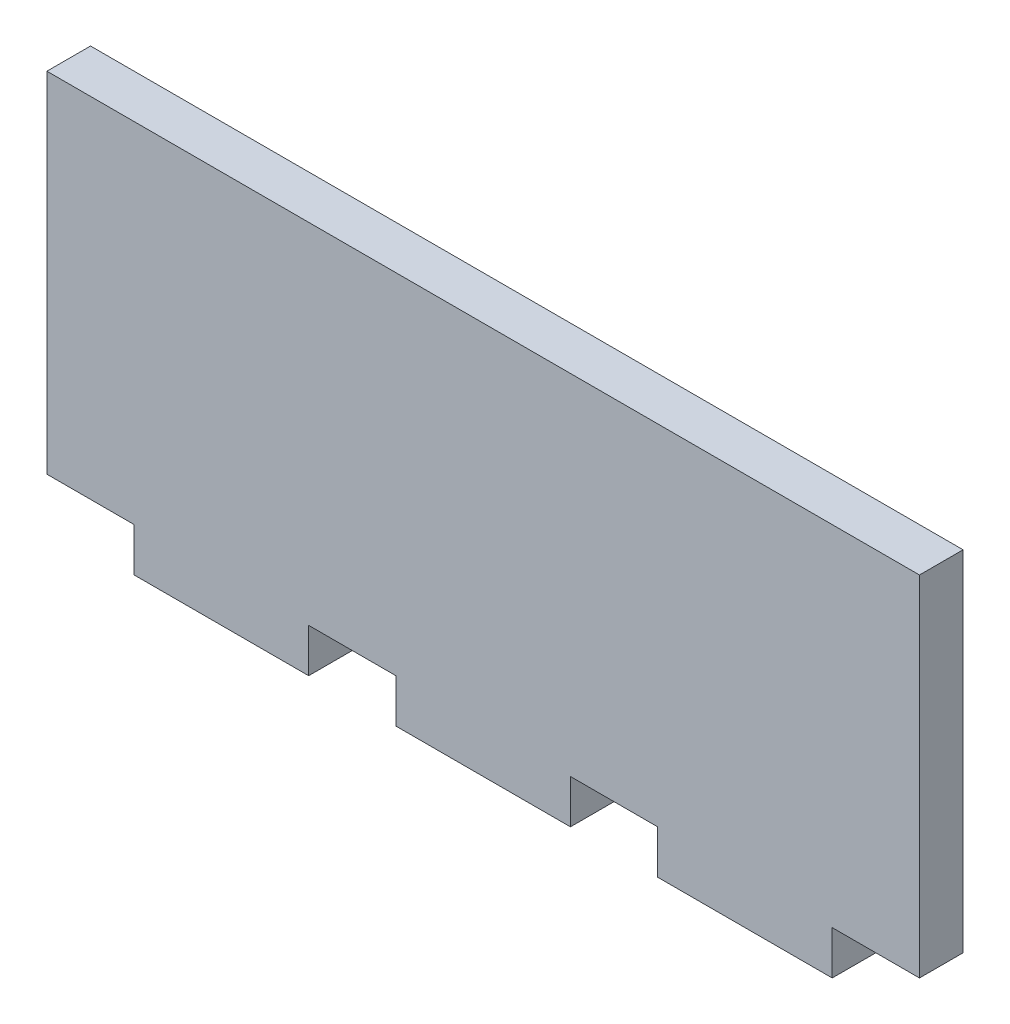
SolidWorks part; units mm, degrees
ref_plane "Plan de face" through (0, 0, 0) normal (0, 0, 1) x (1, 0, 0)
ref_plane "Plan de dessus" through (0, 0, 0) normal (0, 1, 0) x (1, 0, 0)
ref_plane "Plan de droite" through (0, 0, 0) normal (1, 0, 0) x (0, 0, -1)
sketch "Esquisse1" plane through (0, 0, 0) normal (0, 0, 1) x (1, 0, 0)
  line L0 (0, 33.3756) -> (0, -23.9848) construction
  line L1 (-50, 22.5) -> (50, 22.5)
  line L2 (-50, 22.5) -> (-50, -17.5)
  line L4 (50, 22.5) -> (50, -17.5)
  line L9 (-40, -22.5) -> (-20, -22.5)
  line L13 (-50, -17.5) -> (-40, -17.5)
  line L14 (-40, -22.5) -> (-40, -17.5)
  line L15 (40, -22.5) -> (40, -17.5)
  line L16 (50, -17.5) -> (40, -17.5)
  line L17 (20, -22.5) -> (20, -17.5)
  line L19 (-10, -22.5) -> (-10, -17.5)
  line L20 (-10, -17.5) -> (-20, -17.5)
  line L21 (-20, -22.5) -> (-20, -17.5)
  line L22 (10, -22.5) -> (10, -17.5)
  line L23 (10, -17.5) -> (20, -17.5)
  line L27 (-10, -22.5) -> (10, -22.5)
  line L28 (20, -22.5) -> (40, -22.5)
  point P1 (-45, -17.5)
  point P2 (-15, -17.5)
  dimension "D1" = 20
  dimension "D2" = 10
  dimension "D3" = 10
  dimension "D4" = 5
  dimension "D5" = 50
  dimension "D6" = 22.5
  dimension "D7" = 5
  dimension "D8" = 45
extrude "Boss.-Extru.1" add sketch "Esquisse1" along normal blind 5
